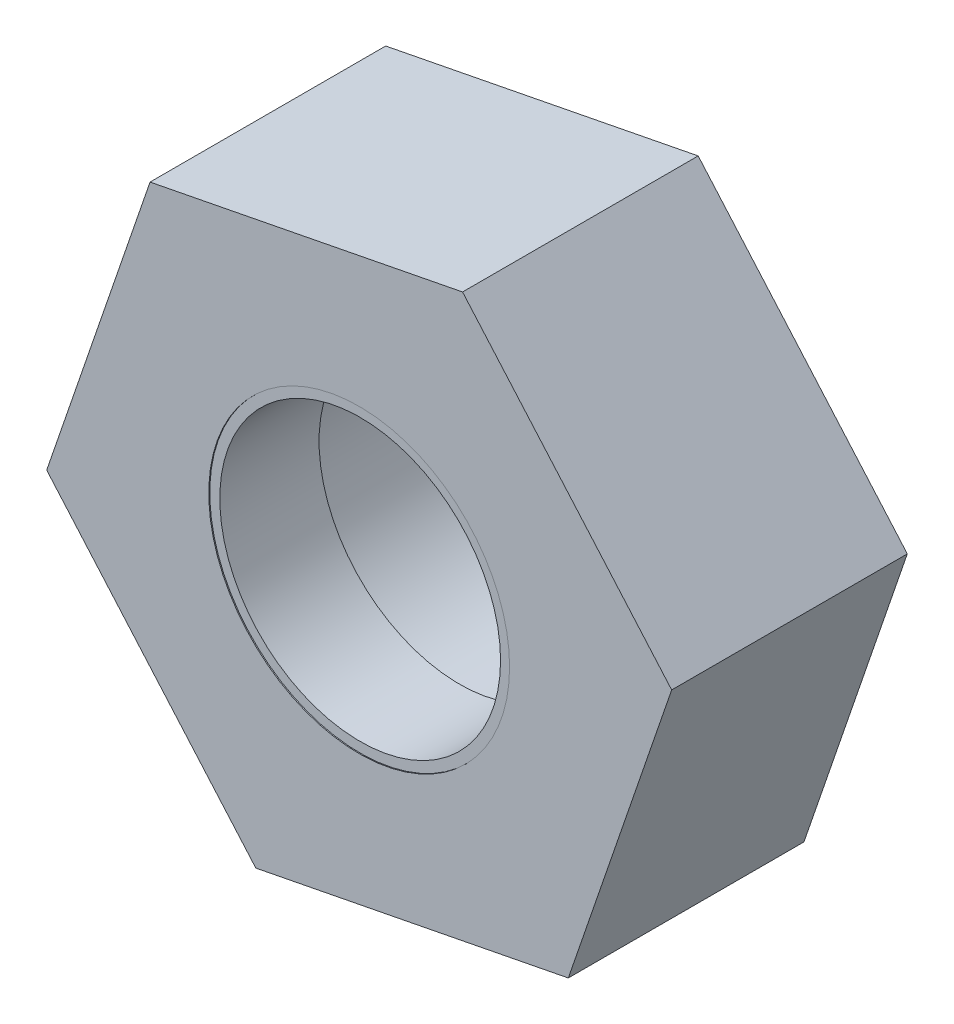
SolidWorks part; units mm, degrees
ref_plane "Front Plane" through (0, 0, 0) normal (0, 0, 1) x (1, 0, 0)
ref_plane "Top Plane" through (0, 0, 0) normal (0, 1, 0) x (1, 0, 0)
ref_plane "Right Plane" through (0, 0, 0) normal (1, 0, 0) x (0, 0, -1)
sketch "Sketch1" plane through (0, 0, 0) normal (0, 0, 1) x (1, 0, 0)
  line L1 (2.0856, -2.3945) -> (3.1165, 0.609)
  line L2 (3.1165, 0.609) -> (1.0309, 3.0034)
  line L3 (1.0309, 3.0034) -> (-2.0856, 2.3945)
  line L4 (-2.0856, 2.3945) -> (-3.1165, -0.609)
  line L5 (-3.1165, -0.609) -> (-1.0309, -3.0034)
  line L6 (-1.0309, -3.0034) -> (2.0856, -2.3945)
  circle A0 centre (0, 0) radius 1.5
  circle A1 centre (0, 0) radius 2.75 construction
  dimension "D1" = 3
  dimension "D2" = 5.5
extrude "Boss-Extrude1" add sketch "Sketch1" along normal blind 2.35
sketch "Sketch2" plane through (0, 0, 2.35) normal (0, 0, 1) x (1, 0, 0)
  circle A0 centre (0, 0) radius 1.4
  circle A1 centre (0, 0) radius 1.5
  dimension "D1" = 2.8
extrude "Boss-Extrude2" add sketch "Sketch2" against normal blind 1
sketch "Sketch3" plane through (0, 0, 2.35) normal (0, 0, 1) x (1, 0, 0)
  circle A0 centre (0, 0) radius 1.5
  circle A1 centre (0, 0) radius 1.4
  dimension "D1" = 3
extrude "Cut-Extrude1" cut sketch "Sketch3" against normal blind 0.01
